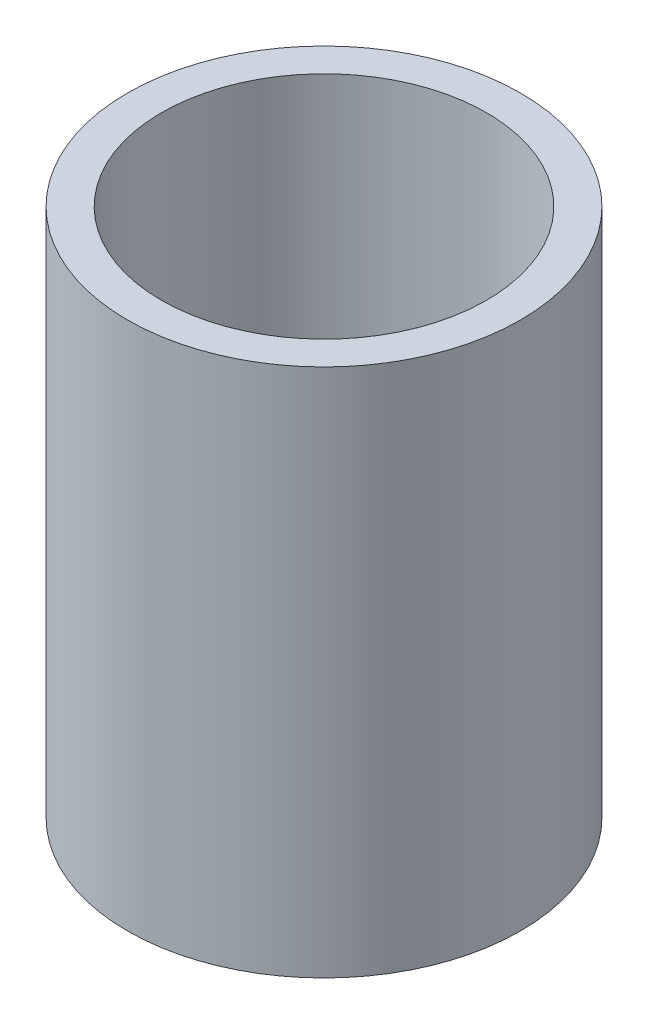
SolidWorks part; units mm, degrees
material "PMMA"
ref_plane "Front Plane" through (0, 0, 0) normal (0, 0, 1) x (1, 0, 0)
ref_plane "Top Plane" through (0, 0, 0) normal (0, 1, 0) x (1, 0, 0)
ref_plane "Right Plane" through (0, 0, 0) normal (1, 0, 0) x (0, 0, -1)
sketch "Sketch1" plane through (0, 0, 0) normal (0, 1, 0) x (1, 0, 0)
  circle A0 centre (0, 0) radius 13
  circle A1 centre (0, 0) radius 10.75
  dimension "D1" = 26
  dimension "D2" = 21.5
extrude "Boss-Extrude1" add sketch "Sketch1" along normal blind 35
sketch3d "3DSketch1"
  point P0 (-15, 35, 14.9746)
